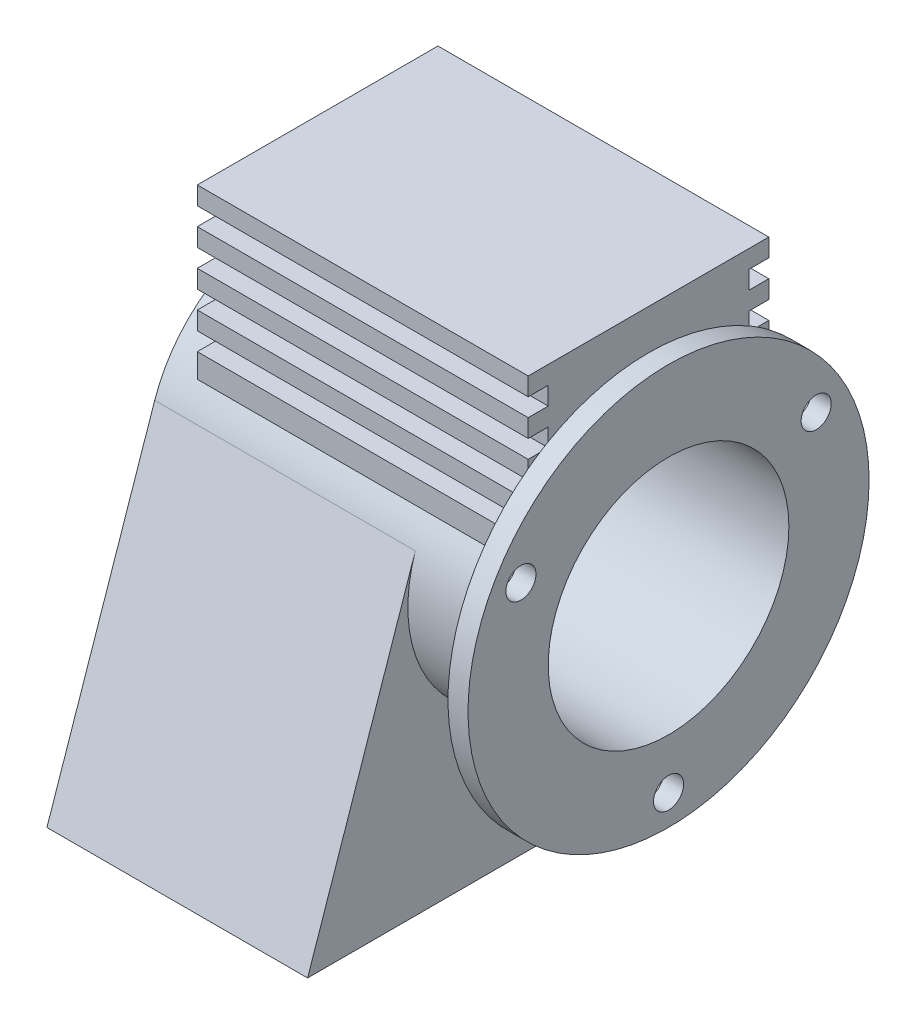
SolidWorks part; units mm, degrees
ref_plane "Front Plane" through (0, 0, 0) normal (0, 0, 1) x (1, 0, 0)
ref_plane "Top Plane" through (0, 0, 0) normal (0, 1, 0) x (1, 0, 0)
ref_plane "Right Plane" through (0, 0, 0) normal (1, 0, 0) x (0, 0, -1)
sketch "Sketch1" plane through (0, 0, 0) normal (1, 0, 0) x (0, 0, -1)
  line L0 (0, 0) -> (0, -171.45) construction
  line L1 (-152.4, -171.45) -> (152.4, -171.45)
  line L2 (-152.4, -171.45) -> (-84.1413, 28.6959)
  line L3 (152.4, -171.45) -> (84.1413, 28.6959)
  arc A0 (84.1413, 28.6959) -> (-84.1413, 28.6959) centre (0, 0) ccw
  dimension "D3" = 177.8
  dimension "D2" = 304.8
extrude "Boss-Extrude1" add sketch "Sketch1" along normal blind 165.1
sketch "Sketch2" plane through (0, 0, 0) normal (-1, 0, 0) x (0, 0, 1)
  circle A0 centre (0, 0) radius 88.9
  dimension "D1" = 177.8
extrude "Boss-Extrude2" add sketch "Sketch2" against normal blind 228.6
sketch "Sketch3" plane through (228.6, 0, 0) normal (1, 0, 0) x (0, 0, -1)
  circle A0 centre (0, 0) radius 127
  dimension "D1" = 254
extrude "Boss-Extrude3" add sketch "Sketch3" along normal blind 12.7
sketch "Sketch4" plane through (228.6, 0, 0) normal (-1, 0, 0) x (0, 0, 1)
  line L0 (0, 0) -> (0, 152.4) construction
  line L2 (-76.2, 152.4) -> (76.2, 152.4)
  line L3 (-76.2, 152.4) -> (-76.2, 0)
  line L4 (-76.2, 0) -> (76.2, 0)
  line L5 (76.2, 152.4) -> (76.2, 0)
  dimension "D1" = 152.4
  dimension "D2" = 152.4
  dimension "D3" = 152.4
extrude "Boss-Extrude4" add sketch "Sketch4" along normal blind 209.55
sketch "Sketch5" plane through (19.05, 0, 0) normal (-1, 0, 0) x (0, 0, 1)
  line L0 (76.2, 152.4) -> (-76.2, 152.4) construction
  line L2 (-88.9, 140.97) -> (-63.5, 140.97)
  line L3 (-88.9, 140.97) -> (-88.9, 129.54)
  line L4 (-88.9, 129.54) -> (-63.5, 129.54)
  line L5 (-63.5, 140.97) -> (-63.5, 129.54)
  line L7 (-76.2, 152.4) -> (-76.2, 45.7905) construction
  dimension "D1" = 11.43
  dimension "D2" = 11.43
  dimension "D3" = 12.7
extrude "Cut-Extrude1" cut sketch "Sketch5" against normal blind 209.55
pattern_linear "LPattern1" count 4 spacing 22.86 along (0, -1, 0) of "Cut-Extrude1"
mirror "Mirror1" about plane through (0, 0, 0) normal (0, 0, 1) of "LPattern1", "Cut-Extrude1"
sketch "Sketch7" plane through (241.3, 0, 0) normal (1, 0, 0) x (0, 0, -1)
  circle A0 centre (0, 0) radius 76.2
  dimension "D1" = 152.4
extrude "Cut-Extrude2" cut sketch "Sketch7" against normal blind 228.6
sketch "Sketch8" plane through (12.7, 0, 0) normal (1, 0, 0) x (0, 0, -1)
  circle A0 centre (0, 0) radius 19.05
  dimension "D1" = 38.1
extrude "Cut-Extrude3" cut sketch "Sketch8" against normal blind 228.6
sketch "Sketch9" plane through (241.3, 0, 0) normal (1, 0, 0) x (0, 0, -1)
  circle A0 centre (0, 0) radius 107.95 construction
  circle A1 centre (0, -107.95) radius 9.525
  circle A2 centre (-93.4874, 53.975) radius 9.525
  circle A3 centre (93.4874, 53.975) radius 9.525
  point P12 (0, 0)
  dimension "D1" = 215.9
  dimension "D2" = 19.05
  dimension "D3" = 3
extrude "Cut-Extrude5" cut sketch "Sketch9" against normal blind 50.8
